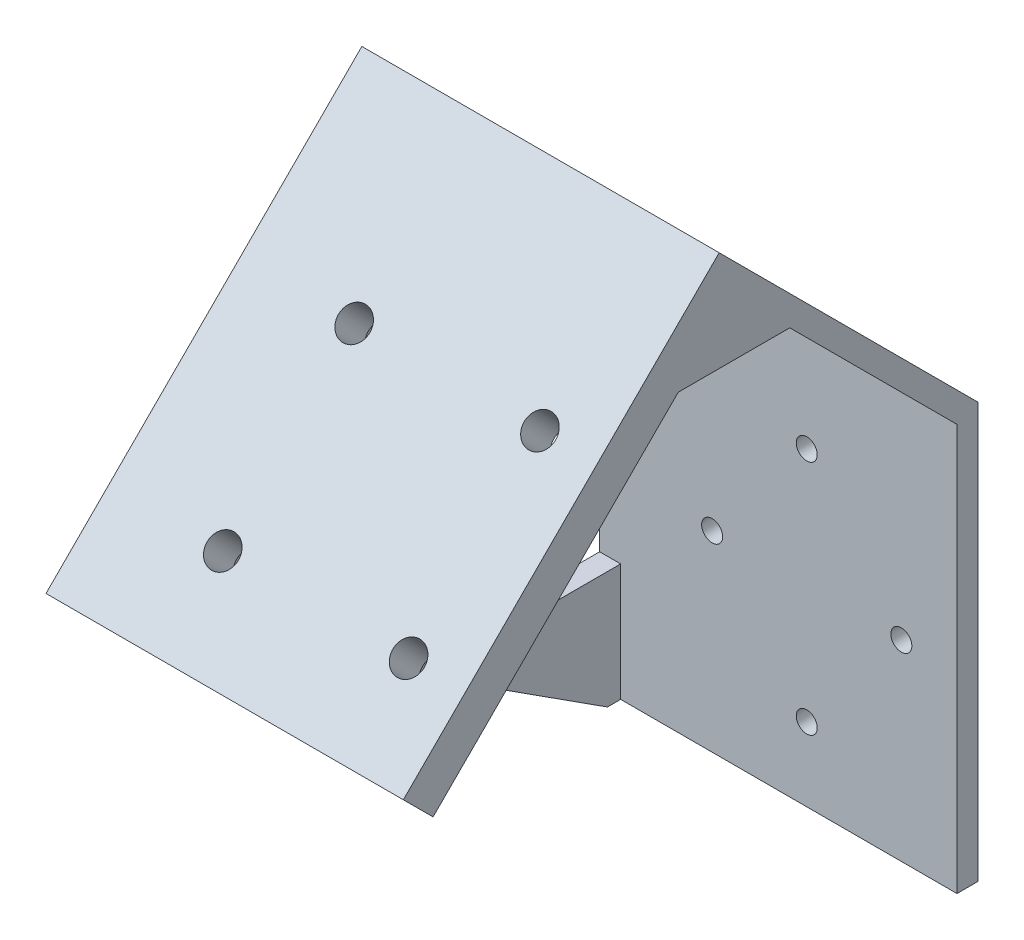
SolidWorks part; units mm, degrees
ref_plane "Front Plane" through (0, 0, 0) normal (0, 0, 1) x (1, 0, 0)
ref_plane "Top Plane" through (0, 0, 0) normal (0, 1, 0) x (1, 0, 0)
ref_plane "Right Plane" through (0, 0, 0) normal (1, 0, 0) x (0, 0, -1)
sketch "Sketch1" plane through (0, 0, 0) normal (1, 0, 0) x (0, 0, -1)
  line L0 (22.3044, 10.5668) -> (22.3044, 87.8961)
  line L5 (-83.0545, 78.7038) -> (-22.9504, 138.8078)
  line L6 (22.3044, 10.5668) -> (26.3044, 10.5668)
  line L8 (26.3044, 10.5668) -> (26.3044, 89.553)
  line L9 (26.3044, 89.553) -> (-22.9504, 138.8078)
  line L10 (-83.0545, 78.7038) -> (-77.3976, 73.0469)
  line L11 (-77.3976, 73.0469) -> (-20.122, 130.3225)
  line L12 (-20.122, 130.3225) -> (22.3044, 87.8961)
  line L13 (22.3044, 10.5668) -> (22.3044, 83.5668) construction
  line L14 (-86.9269, 74.8313) -> (-30.3584, 131.3998) construction
  line L15 (14.3044, 10.5668) -> (22.3044, 10.5668) construction
  dimension "D1" = 0
  dimension "D2" = 4
  dimension "D3" = 85
  dimension "D4" = 4
  dimension "D5" = 0
  dimension "D6" = 8
  dimension "D7" = 0
  dimension "D8" = 60
  dimension "D9" = 135
extrude "Boss-Extrude1" add sketch "Sketch1" along normal blind 37 and the other way blind 27
sketch "Sketch2" plane through (0, 0, -22.3044) normal (0, 0, 1) x (1, 0, 0)
  line L0 (8.41, 69.5668) -> (8.41, 24.5668) construction
  line L1 (-9.59, 47.0668) -> (26.41, 47.0668) construction
  circle A0 centre (8.41, 69.5668) radius 2
  circle A1 centre (26.41, 47.0668) radius 2
  circle A2 centre (8.41, 24.5668) radius 2
  circle A3 centre (-9.59, 47.0668) radius 2
  circle A4 centre (-9.59, 47.0668) radius 2.75 construction
  point P4 (8.41, 47.0668)
  point P7 (8.41, 47.0668)
  dimension "D1" = 4
  dimension "D6" = 0
  dimension "D2" = 45
  dimension "D3" = 36
  dimension "D5" = 8.41
extrude "Cut-Extrude1" cut sketch "Sketch2" against normal through all
sketch "Sketch12" plane through (-27, 0, 0) normal (-1, 0, 0) x (0, 0, 1)
  line L0 (-19.7923, 10.5668) -> (77.3976, 73.0469)
  line L1 (77.3976, 73.0469) -> (83.0545, 78.7038)
  line L2 (83.0545, 78.7038) -> (22.9504, 138.8078)
  line L3 (22.9504, 138.8078) -> (-26.3044, 89.553)
  line L5 (-22.3044, 87.8961) -> (5.6956, 87.8961)
  line L6 (5.6956, 87.8961) -> (5.6956, 32.8961)
  line L7 (5.6956, 32.8961) -> (-22.3044, 32.8961)
  line L8 (-22.3044, 87.8961) -> (-22.3044, 10.5668) construction
  line L10 (-26.3044, 10.5668) -> (-26.3044, 89.553)
  line L11 (-22.3044, 87.8961) -> (-22.3044, 32.8961)
  line L12 (-22.3044, 87.8961) -> (-22.3044, 32.8961)
  line L13 (-26.3044, 10.5668) -> (-19.7923, 10.5668)
  line M4 (-26.3044, 10.5668) -> (-22.3044, 10.5668)
  line M5 (-22.3044, 10.5668) -> (-22.3044, 87.8961)
  line M6 (-22.3044, 87.8961) -> (20.122, 130.3225)
  line M7 (20.122, 130.3225) -> (77.3976, 73.0469)
  line M8 (77.3976, 73.0469) -> (83.0545, 78.7038)
  line M9 (83.0545, 78.7038) -> (22.9504, 138.8078)
  line M10 (22.9504, 138.8078) -> (-26.3044, 89.553)
  line M11 (-26.3044, 89.553) -> (-26.3044, 10.5668)
  dimension "D1" = 28
  dimension "D2" = 5
  dimension "D3" = 55
extrude "Boss-Extrude2" add sketch "Sketch12" along normal blind 4 contours L13 L0 L5 L6 L7 M5 M7 M6 | M11 M4 M5 M6 M7 M8 M9 M10
chamfer "Chamfer1" distance 15 angle 45 1 edges at (5, 130.3225, 20.122)
sketch "Sketch4" plane through (0, 204.7332, -42.975) normal (0, -0.7071, -0.7071) x (1, 0, 0)
  line L0 (26.0877, 126.0314) -> (-9.2677, 161.3867) construction
  line L1 (-9.2677, 126.0314) -> (26.0877, 126.0314) construction
  circle A0 centre (8.41, 143.709) radius 25 construction
  circle A1 centre (-9.2677, 126.0314) radius 3
  circle A2 centre (-9.2677, 161.3867) radius 3
  circle A3 centre (26.0877, 161.3867) radius 3
  circle A4 centre (26.0877, 126.0314) radius 3
  circle A5 centre (-9.2677, 126.0314) radius 5 construction
  point P2 (14.5399, 168.4815)
  point P3 (24.7976, 126.0314)
  point P17 (8.41, 143.709)
  dimension "D1" = 50
  dimension "D2" = 6
  dimension "D4" = 10
  dimension "D7" = 45
  dimension "D3" = 4
extrude "Cut-Extrude7" cut sketch "Sketch4" along normal blind 20
chamfer "Chamfer2" distance 10 angle 45 1 edges at (-27, 96.3814, 54.0631)
